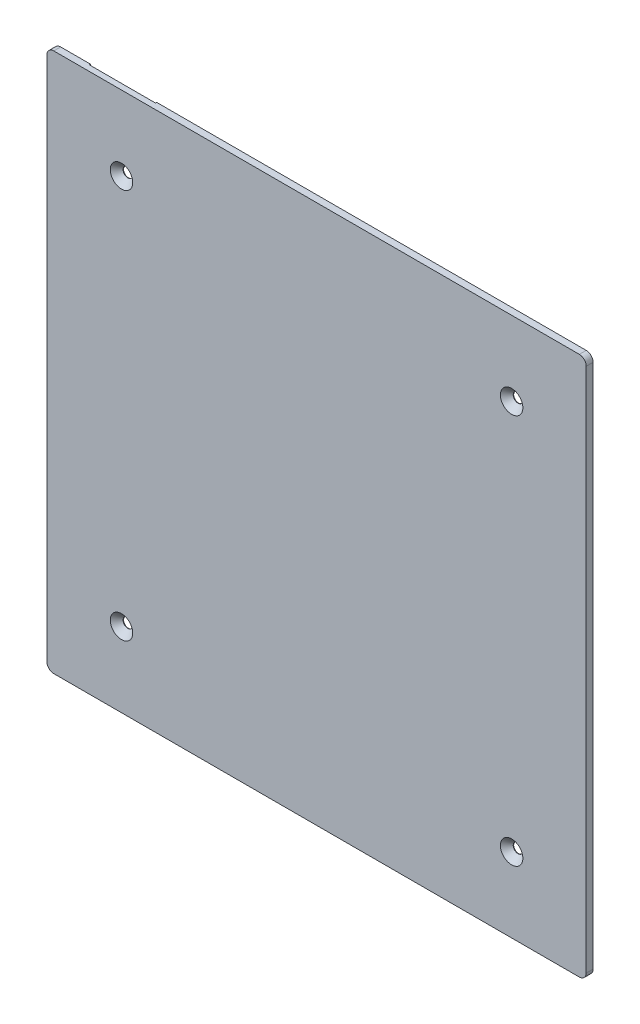
SolidWorks part; units mm, degrees
ref_plane "Alzado" through (0, 0, 0) normal (0, 0, 1) x (1, 0, 0)
ref_plane "Planta" through (0, 0, 0) normal (0, 1, 0) x (1, 0, 0)
ref_plane "Vista lateral" through (0, 0, 0) normal (1, 0, 0) x (0, 0, -1)
ref_plane "Plano1" through (0, 0, 0) normal (0, 0, -1) x (-1, 0, 0)
sketch "Croquis1" plane through (0, 0, 0) normal (0, 0, -1) x (-1, 0, 0)
  line L0 (117.5, -117.5) -> (117.5, 117.5)
  line L1 (117.5, 117.5) -> (-117.5, 117.5)
  line L2 (-117.5, 117.5) -> (-117.5, -117.5)
  line L3 (-117.5, -117.5) -> (117.5, -117.5)
extrude "Saliente-Extruir1" add sketch "Croquis1" against normal blind 3
sketch "Croquis2" plane through (0, 0, 0) normal (0, 0, -1) x (-1, 0, 0)
  line L0 (72.6508, 117.5) -> (72.6508, 106.0508)
  line L1 (72.6508, 106.0508) -> (101.4629, 106.0508)
  line L2 (101.4629, 106.0508) -> (101.4629, 117.5)
  line L3 (101.4629, 117.5) -> (72.6508, 117.5)
extrude "Cortar-Extruir1" cut sketch "Croquis2" against normal blind 0.5
hole_wizard "Avellanado para tornillo con cabeza plana de M3.51" positions "Croquis4" profile "Croquis3" countersink size "M3.5" standard "Ansi Metric"
sketch "Croquis4" plane through (0, 0, 3) normal (0, 0, 1) x (1, 0, 0)
  point P0 (-85, -85)
  point P1 (85, -85)
  point P2 (85, 85)
  point P3 (-85, 85)
sketch "Croquis3" plane through (-85, -85, 3) normal (1, 0, 0) x (0, -1, 0)
  line L0 (0, 0) -> (0, 3)
  line L1 (0, 3) -> (2.1, 3)
  line L2 (2.1, 3) -> (2.1, 2.8)
  line L3 (2.1, 2.8) -> (4.9, 0)
  line L5 (4.9, 0) -> (0, 0)
  line L6 (-2.1, 2.8) -> (-4.9, 0) construction
  line L11 (0, -6.35) -> (0, 107.95) construction
  dimension "Diámetro de taladro hasta el siguiente" = 4.2
  dimension "Profundidad de taladro hasta el siguiente" = 3
  dimension "Diámetro de avellanado cercano" = 9.8
  dimension "Ángulo de avellanado cercano" = 90
fillet "Redondeo1" radius 3 4 edges at (-117.5, -117.5, 1.5) (117.5, -117.5, 1.5) (-117.5, 117.5, 1.5) (117.5, 117.5, 1.5)
